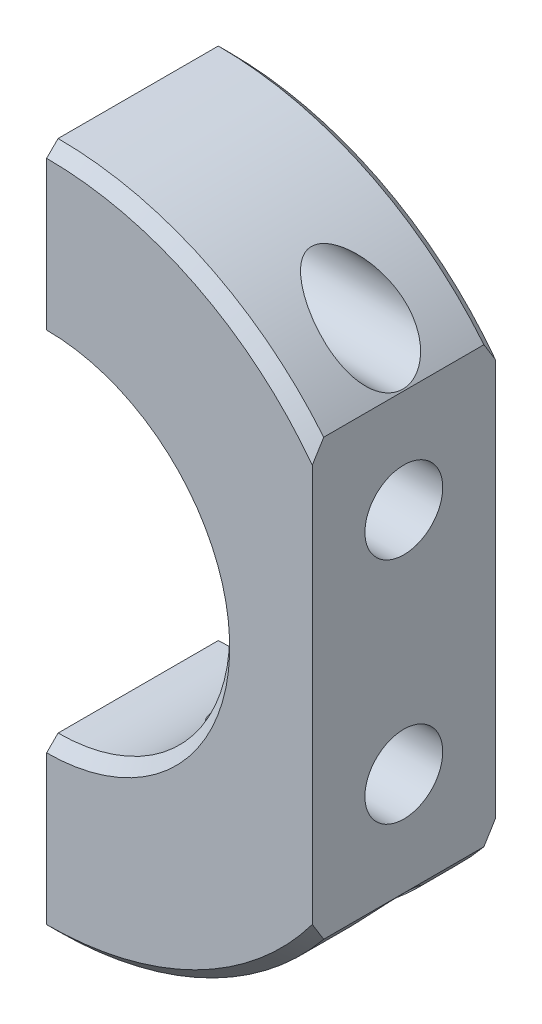
SolidWorks part; units mm, degrees
ref_plane "前视基准面" through (0, 0, 0) normal (0, 0, 1) x (1, 0, 0)
ref_plane "上视基准面" through (0, 0, 0) normal (0, 1, 0) x (1, 0, 0)
ref_plane "右视基准面" through (0, 0, 0) normal (1, 0, 0) x (0, 0, -1)
sketch "草图1" plane through (0, 0, 0) normal (0, 0, 1) x (1, 0, 0)
  line L0 (-6.7808, 23.0052) -> (-6.7808, 15.5052)
  line L1 (-6.7808, 0.5052) -> (-6.7808, -6.9948)
  line L2 (-6.7808, 8.0052) -> (7.8274, 8.0052) construction
  line L3 (4.8274, 17.5052) -> (4.8274, -1.4948)
  arc A0 (-6.7808, -6.9948) -> (4.8274, -1.4948) centre (-6.7808, 8.0052) ccw
  arc A1 (-6.7808, 0.5052) -> (-6.7808, 15.5052) centre (-6.7808, 8.0052) ccw
  arc A2 (4.8274, 17.5052) -> (-6.7808, 23.0052) centre (-6.7808, 8.0052) ccw
  point P9 (4.8274, 8.0052)
  dimension "D1" = 30
  dimension "D2" = 15
  dimension "D3" = 9.5
extrude "凸台-拉伸1" add sketch "草图1" along normal blind 8
sketch "草图2" plane through (-6.7808, 0, 0) normal (-1, 0, 0) x (0, 0, 1)
  circle A0 centre (4, 19.2552) radius 3
  circle A1 centre (4, 19.2552) radius 1.7
  dimension "D1" = 6
  dimension "D2" = 3.4
extrude "切除-拉伸2" cut sketch "草图2" against normal blind 15 contours A1
sketch "草图3" plane through (-6.7808, 0, 0) normal (-1, 0, 0) x (0, 0, 1)
  circle A0 centre (4, -3.2448) radius 3
  circle A1 centre (4, -3.2448) radius 1.7
  dimension "D1" = 6
  dimension "D2" = 3.4
extrude "切除-拉伸4" cut sketch "草图3" against normal blind 15 contours A1
chamfer "倒角1" distance 0.5 8 edges at (-0.3582, -5.5502, 0) (-0.3582, -5.5502, 8) (0.7192, 8.0052, 0) (0.7192, 8.0052, 8) (-0.3582, 21.5607, 0) (4.8274, 8.0052, 0) (-0.3582, 21.5607, 8) (4.8274, 8.0052, 8)
sketch "草图4" plane through (4.8274, 0, 0) normal (1, 0, 0) x (0, 0, -1)
  circle A0 centre (-4, 13.0052) radius 1.7
  circle A1 centre (-4, 3.0052) radius 1.7
  dimension "D1" = 3.4
  dimension "D2" = 10
extrude "切除-拉伸5" cut sketch "草图4" against normal blind 10
